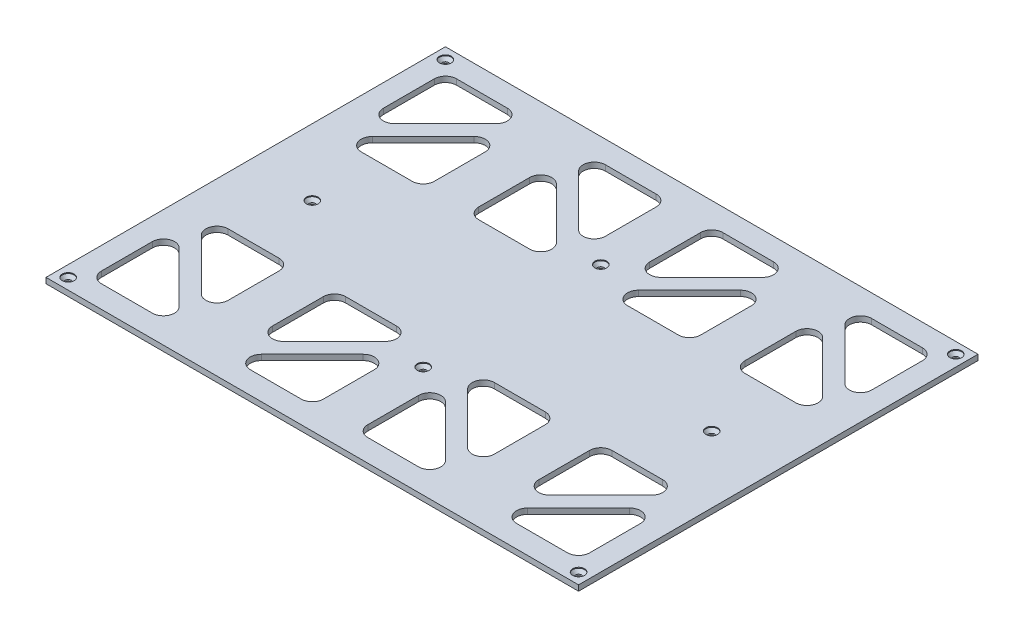
SolidWorks part; units mm, degrees
material "1060 Alloy"
ref_plane "Front Plane" through (0, 0, 0) normal (0, 0, 1) x (1, 0, 0)
ref_plane "Top Plane" through (0, 0, 0) normal (0, 1, 0) x (1, 0, 0)
ref_plane "Right Plane" through (0, 0, 0) normal (1, 0, 0) x (0, 0, -1)
sketch "Sketch2" plane through (0, 0, 0) normal (0, 1, 0) x (1, 0, 0)
  line L0 (-240.3287, 78.4637) -> (-240.3287, 20.2243)
  line L1 (-265.7287, 116.5637) -> (343.8713, 116.5637)
  line L2 (-265.7287, 116.5637) -> (-265.7287, -340.6363)
  line L3 (-265.7287, -340.6363) -> (343.8713, -340.6363)
  line L4 (343.8713, 116.5637) -> (343.8713, -340.6363)
  line L5 (-218.6484, 11.244) -> (-160.4089, 69.4835)
  line L6 (-169.3892, 91.1637) -> (-227.6287, 91.1637)
  line L7 (-218.6484, -14.156) -> (-160.4089, 44.0835)
  line L8 (-138.7287, 35.1032) -> (-138.7287, -23.1363)
  line L9 (-151.4287, -35.8363) -> (-209.6682, -35.8363)
  line L10 (39.0713, 116.5637) -> (39.0713, -340.6363) construction
  line L11 (343.8713, -112.0363) -> (-265.7287, -112.0363) construction
  line L12 (-113.3287, 116.5637) -> (-113.3287, -340.6363) construction
  line L13 (-75.2287, -35.8363) -> (-16.9892, -35.8363)
  line L14 (-87.9287, 35.1032) -> (-87.9287, -23.1363)
  line L15 (-8.0089, -14.156) -> (-66.2484, 44.0835)
  line L16 (-57.2682, 91.1637) -> (0.9713, 91.1637)
  line L17 (-8.0089, 11.244) -> (-66.2484, 69.4835)
  line L18 (13.6713, 78.4637) -> (13.6713, 20.2243)
  line L19 (64.4713, 78.4637) -> (64.4713, 20.2243)
  line L20 (86.1516, 11.244) -> (144.3911, 69.4835)
  line L21 (135.4108, 91.1637) -> (77.1713, 91.1637)
  line L22 (86.1516, -14.156) -> (144.3911, 44.0835)
  line L23 (166.0713, 35.1032) -> (166.0713, -23.1363)
  line L24 (153.3713, -35.8363) -> (95.1318, -35.8363)
  line L25 (229.5713, -35.8363) -> (287.8108, -35.8363)
  line L26 (216.8713, 35.1032) -> (216.8713, -23.1363)
  line L27 (296.7911, -14.156) -> (238.5516, 44.0835)
  line L28 (247.5318, 91.1637) -> (305.7713, 91.1637)
  line L29 (296.7911, 11.244) -> (238.5516, 69.4835)
  line L30 (318.4713, 78.4637) -> (318.4713, 20.2243)
  line L31 (318.4713, -302.5363) -> (318.4713, -244.2968)
  line L32 (296.7911, -235.3165) -> (238.5516, -293.556)
  line L33 (247.5318, -315.2363) -> (305.7713, -315.2363)
  line L34 (296.7911, -209.9165) -> (238.5516, -268.156)
  line L35 (216.8713, -259.1757) -> (216.8713, -200.9363)
  line L36 (229.5713, -188.2363) -> (287.8108, -188.2363)
  line L37 (153.3713, -188.2363) -> (95.1318, -188.2363)
  line L38 (166.0713, -259.1757) -> (166.0713, -200.9363)
  line L39 (86.1516, -209.9165) -> (144.3911, -268.156)
  line L40 (135.4108, -315.2363) -> (77.1713, -315.2363)
  line L41 (86.1516, -235.3165) -> (144.3911, -293.556)
  line L42 (64.4713, -302.5363) -> (64.4713, -244.2968)
  line L43 (13.6713, -302.5363) -> (13.6713, -244.2968)
  line L44 (-8.0089, -235.3165) -> (-66.2484, -293.556)
  line L45 (-57.2682, -315.2363) -> (0.9713, -315.2363)
  line L46 (-8.0089, -209.9165) -> (-66.2484, -268.156)
  line L47 (-87.9287, -259.1757) -> (-87.9287, -200.9363)
  line L48 (-75.2287, -188.2363) -> (-16.9892, -188.2363)
  line L49 (-151.4287, -188.2363) -> (-209.6682, -188.2363)
  line L50 (-138.7287, -259.1757) -> (-138.7287, -200.9363)
  line L51 (-218.6484, -209.9165) -> (-160.4089, -268.156)
  line L52 (-169.3892, -315.2363) -> (-227.6287, -315.2363)
  line L53 (-218.6484, -235.3165) -> (-160.4089, -293.556)
  line L54 (-240.3287, -302.5363) -> (-240.3287, -244.2968)
  arc A0 (-160.4089, 44.0835) -> (-138.7287, 35.1032) centre (-151.4287, 35.1032) cw
  arc A1 (-138.7287, -23.1363) -> (-151.4287, -35.8363) centre (-151.4287, -23.1363) cw
  arc A2 (-218.6484, -14.156) -> (-209.6682, -35.8363) centre (-209.6682, -23.1363) ccw
  arc A3 (-240.3287, 20.2243) -> (-218.6484, 11.244) centre (-227.6287, 20.2243) ccw
  arc A4 (-160.4089, 69.4835) -> (-169.3892, 91.1637) centre (-169.3892, 78.4637) ccw
  arc A5 (-240.3287, 78.4637) -> (-227.6287, 91.1637) centre (-227.6287, 78.4637) cw
  arc A6 (13.6713, 78.4637) -> (0.9713, 91.1637) centre (0.9713, 78.4637) ccw
  arc A7 (-66.2484, 69.4835) -> (-57.2682, 91.1637) centre (-57.2682, 78.4637) cw
  arc A8 (13.6713, 20.2243) -> (-8.0089, 11.244) centre (0.9713, 20.2243) cw
  arc A9 (-8.0089, -14.156) -> (-16.9892, -35.8363) centre (-16.9892, -23.1363) cw
  arc A10 (-87.9287, -23.1363) -> (-75.2287, -35.8363) centre (-75.2287, -23.1363) ccw
  arc A11 (-66.2484, 44.0835) -> (-87.9287, 35.1032) centre (-75.2287, 35.1032) ccw
  arc A12 (144.3911, 44.0835) -> (166.0713, 35.1032) centre (153.3713, 35.1032) cw
  arc A13 (166.0713, -23.1363) -> (153.3713, -35.8363) centre (153.3713, -23.1363) cw
  arc A14 (86.1516, -14.156) -> (95.1318, -35.8363) centre (95.1318, -23.1363) ccw
  arc A15 (64.4713, 20.2243) -> (86.1516, 11.244) centre (77.1713, 20.2243) ccw
  arc A16 (144.3911, 69.4835) -> (135.4108, 91.1637) centre (135.4108, 78.4637) ccw
  arc A17 (64.4713, 78.4637) -> (77.1713, 91.1637) centre (77.1713, 78.4637) cw
  arc A18 (318.4713, 78.4637) -> (305.7713, 91.1637) centre (305.7713, 78.4637) ccw
  arc A19 (238.5516, 69.4835) -> (247.5318, 91.1637) centre (247.5318, 78.4637) cw
  arc A20 (318.4713, 20.2243) -> (296.7911, 11.244) centre (305.7713, 20.2243) cw
  arc A21 (296.7911, -14.156) -> (287.8108, -35.8363) centre (287.8108, -23.1363) cw
  arc A22 (216.8713, -23.1363) -> (229.5713, -35.8363) centre (229.5713, -23.1363) ccw
  arc A23 (238.5516, 44.0835) -> (216.8713, 35.1032) centre (229.5713, 35.1032) ccw
  arc A24 (238.5516, -268.156) -> (216.8713, -259.1757) centre (229.5713, -259.1757) cw
  arc A25 (216.8713, -200.9363) -> (229.5713, -188.2363) centre (229.5713, -200.9363) cw
  arc A26 (296.7911, -209.9165) -> (287.8108, -188.2363) centre (287.8108, -200.9363) ccw
  arc A27 (318.4713, -244.2968) -> (296.7911, -235.3165) centre (305.7713, -244.2968) ccw
  arc A28 (238.5516, -293.556) -> (247.5318, -315.2363) centre (247.5318, -302.5363) ccw
  arc A29 (318.4713, -302.5363) -> (305.7713, -315.2363) centre (305.7713, -302.5363) cw
  arc A30 (64.4713, -302.5363) -> (77.1713, -315.2363) centre (77.1713, -302.5363) ccw
  arc A31 (144.3911, -293.556) -> (135.4108, -315.2363) centre (135.4108, -302.5363) cw
  arc A32 (64.4713, -244.2968) -> (86.1516, -235.3165) centre (77.1713, -244.2968) cw
  arc A33 (86.1516, -209.9165) -> (95.1318, -188.2363) centre (95.1318, -200.9363) cw
  arc A34 (166.0713, -200.9363) -> (153.3713, -188.2363) centre (153.3713, -200.9363) ccw
  arc A35 (144.3911, -268.156) -> (166.0713, -259.1757) centre (153.3713, -259.1757) ccw
  arc A36 (-66.2484, -268.156) -> (-87.9287, -259.1757) centre (-75.2287, -259.1757) cw
  arc A37 (-87.9287, -200.9363) -> (-75.2287, -188.2363) centre (-75.2287, -200.9363) cw
  arc A38 (-8.0089, -209.9165) -> (-16.9892, -188.2363) centre (-16.9892, -200.9363) ccw
  arc A39 (13.6713, -244.2968) -> (-8.0089, -235.3165) centre (0.9713, -244.2968) ccw
  arc A40 (-66.2484, -293.556) -> (-57.2682, -315.2363) centre (-57.2682, -302.5363) ccw
  arc A41 (13.6713, -302.5363) -> (0.9713, -315.2363) centre (0.9713, -302.5363) cw
  arc A42 (-240.3287, -302.5363) -> (-227.6287, -315.2363) centre (-227.6287, -302.5363) ccw
  arc A43 (-160.4089, -293.556) -> (-169.3892, -315.2363) centre (-169.3892, -302.5363) cw
  arc A44 (-240.3287, -244.2968) -> (-218.6484, -235.3165) centre (-227.6287, -244.2968) cw
  arc A45 (-218.6484, -209.9165) -> (-209.6682, -188.2363) centre (-209.6682, -200.9363) cw
  arc A46 (-138.7287, -200.9363) -> (-151.4287, -188.2363) centre (-151.4287, -200.9363) ccw
  arc A47 (-160.4089, -268.156) -> (-138.7287, -259.1757) centre (-151.4287, -259.1757) ccw
  point P19 (-138.7287, 65.7637)
  point P22 (-138.7287, -35.8363)
  point P25 (-240.3287, -35.8363)
  point P28 (-240.3287, -10.4363)
  point P31 (-138.7287, 91.1637)
  point P34 (-240.3287, 91.1637)
  point P53 (13.6713, 91.1637)
  point P54 (-87.9287, 91.1637)
  point P55 (13.6713, -10.4363)
  point P56 (13.6713, -35.8363)
  point P57 (-87.9287, -35.8363)
  point P58 (-87.9287, 65.7637)
  point P95 (166.0713, 65.7637)
  point P96 (166.0713, -35.8363)
  point P97 (64.4713, -35.8363)
  point P98 (64.4713, -10.4363)
  point P99 (166.0713, 91.1637)
  point P100 (64.4713, 91.1637)
  point P101 (318.4713, 91.1637)
  point P102 (216.8713, 91.1637)
  point P103 (318.4713, -10.4363)
  point P104 (318.4713, -35.8363)
  point P105 (216.8713, -35.8363)
  point P106 (216.8713, 65.7637)
  point P179 (216.8713, -289.8363)
  point P180 (216.8713, -188.2363)
  point P181 (318.4713, -188.2363)
  point P182 (318.4713, -213.6363)
  point P183 (216.8713, -315.2363)
  point P184 (318.4713, -315.2363)
  point P185 (64.4713, -315.2363)
  point P186 (166.0713, -315.2363)
  point P187 (64.4713, -213.6363)
  point P188 (64.4713, -188.2363)
  point P189 (166.0713, -188.2363)
  point P190 (166.0713, -289.8363)
  point P191 (-87.9287, -289.8363)
  point P192 (-87.9287, -188.2363)
  point P193 (13.6713, -188.2363)
  point P194 (13.6713, -213.6363)
  point P195 (-87.9287, -315.2363)
  point P196 (13.6713, -315.2363)
  point P197 (-240.3287, -315.2363)
  point P198 (-138.7287, -315.2363)
  point P199 (-240.3287, -213.6363)
  point P200 (-240.3287, -188.2363)
  point P201 (-138.7287, -188.2363)
  point P202 (-138.7287, -289.8363)
  dimension "D11" = 12.7
  dimension "D1" = 609.6
  dimension "D2" = 457.2
  dimension "D3" = 25.4
  dimension "D4" = 25.4
  dimension "D5" = 101.6
  dimension "D6" = 101.6
  dimension "D7" = 101.6
  dimension "D8" = 101.6
  dimension "D9" = 25.4
  dimension "D10" = 152.4
extrude "Boss-Extrude1" add sketch "Sketch2" along normal blind 6.35
sketch "Sketch3" plane through (0, 6.35, 0) normal (0, 1, 0) x (1, 0, 0)
  line L0 (-265.7287, 116.5637) -> (-265.7287, -340.6363) construction
  line L1 (343.8713, -340.6363) -> (343.8713, 116.5637) construction
  line L2 (343.8713, 116.5637) -> (-265.7287, 116.5637) construction
  line L3 (-265.7287, -340.6363) -> (343.8713, -340.6363) construction
  line L4 (343.8713, -340.6363) -> (343.8713, 116.5637) construction
  point P0 (39.0713, -10.4363)
  point P1 (39.0713, -213.6363)
  point P2 (267.6713, -112.0363)
  point P3 (-189.5287, -112.0363)
  point P4 (-265.7287, -112.0363)
  point P9 (39.0713, 116.5637)
  point P14 (-253.0287, -327.9363)
  point P15 (331.1713, -327.9363)
  point P16 (331.1713, 103.8637)
  point P17 (-253.0287, 103.8637)
  dimension "D1" = 76.2
  dimension "D2" = 76.2
  dimension "D3" = 127
  dimension "D4" = 127
  dimension "D5" = 12.7
  dimension "D6" = 12.7
  dimension "D7" = 12.7
  dimension "D8" = 12.7
  dimension "D9" = 12.7
  dimension "D10" = 12.7
  dimension "D11" = 12.7
  dimension "D12" = 12.7
hole_wizard "CSK for 1/4 Flat Head Socket Cap Screw1" positions "3DSketch1" profile "Sketch5" countersink size "1/4" standard "ANSI Inch" end condition through all
sketch3d "3DSketch1"
  point P0 (-253.0287, 6.35, -103.8637)
  point P3 (-189.5287, 6.35, 112.0363)
  point P6 (-253.0287, 6.35, 327.9363)
  point P9 (39.0713, 6.35, 213.6363)
  point P12 (39.0713, 6.35, 10.4363)
  point P15 (331.1713, 6.35, -103.8637)
  point P18 (267.6713, 6.35, 112.0363)
  point P21 (331.1713, 6.35, 327.9363)
sketch "Sketch5" plane through (-253.0287, 6.35, -103.8637) normal (1, 0, 0) x (0, 0, 1)
  line L0 (0, 0) -> (0, 6.35)
  line L1 (0, 6.35) -> (3.5712, 6.35)
  line L2 (3.5712, 6.35) -> (3.5712, 4.6655)
  line L3 (3.5712, 4.6655) -> (6.7437, 1.016)
  line L4 (6.7437, 1.016) -> (6.7437, 0)
  line L6 (6.7437, 0) -> (0, 0)
  line L7 (-3.5712, 4.6655) -> (-6.7437, 1.016) construction
  line L11 (0, -6.35) -> (0, 107.95) construction
  dimension "Thru Hole Dia." = 7.1425
  dimension "Thru Hole Depth" = 6.35
  dimension "C'Sink Dia." = 13.4874
  dimension "C'Sink Angle" = 82
  dimension "Head Clearance" = 1.016
